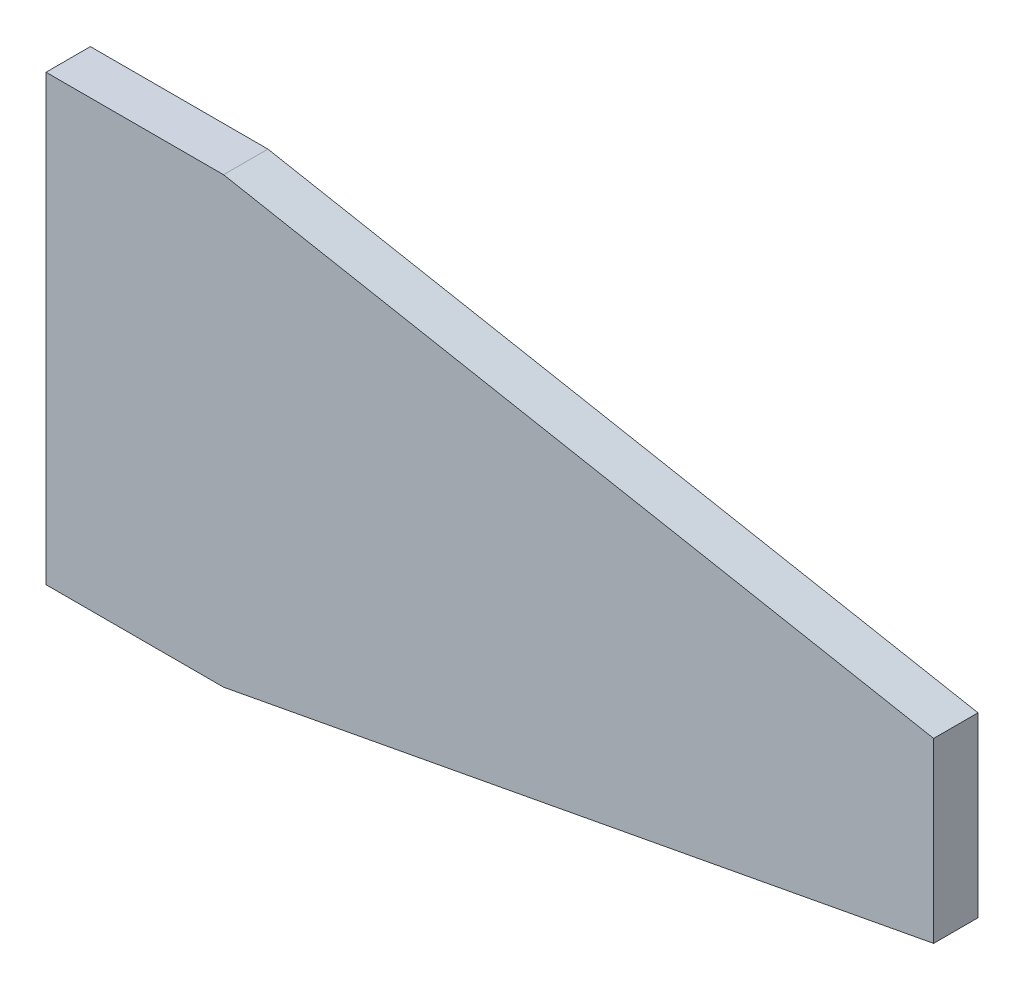
SolidWorks part; units mm, degrees
material "Heavy Pine"
ref_plane "Front Plane" through (0, 0, 0) normal (0, 0, 1) x (1, 0, 0)
ref_plane "Top Plane" through (0, 0, 0) normal (0, 1, 0) x (1, 0, 0)
ref_plane "Right Plane" through (0, 0, 0) normal (1, 0, 0) x (0, 0, -1)
sketch "Sketch1" plane through (0, 0, 0) normal (0, 0, 1) x (1, 0, 0)
  line L0 (200, 20) -> (40, 50)
  line L1 (40, 50) -> (0, 50)
  line L5 (0, -50) -> (40, -50)
  line L6 (40, -50) -> (200, -20)
  line L7 (200, -20) -> (200, 20)
  line L8 (0, 0) -> (200, 0) construction
  line L10 (0, 50) -> (0, -50)
  point P4 (0, 0)
  dimension "D1" = 200
  dimension "D3" = 100
  dimension "D5" = 40
  dimension "D6" = 40
extrude "Boss-Extrude1" add sketch "Sketch1" along normal mid plane 10
